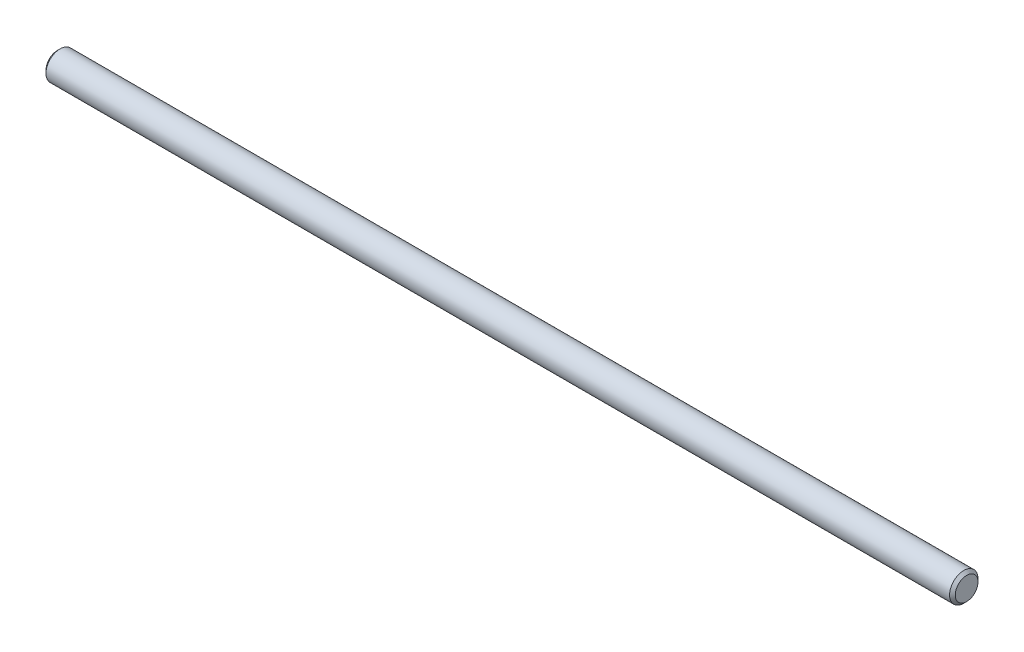
SolidWorks part; units mm, degrees
ref_plane "Front" through (0, 0, 0) normal (0, 0, 1) x (1, 0, 0)
ref_plane "Top" through (0, 0, 0) normal (0, 1, 0) x (1, 0, 0)
ref_plane "Right" through (0, 0, 0) normal (1, 0, 0) x (0, 0, -1)
sketch "Sketch1" plane through (0, 0, 0) normal (0, 0, 1) x (1, 0, 0)
  line L0 (-203.2, 0) -> (203.2, 0) construction
  line L1 (203.2, 6.35) -> (203.2, -6.35) construction
  line L2 (-203.2, 6.35) -> (-203.2, -6.35) construction
  dimension "Length" = 406.4
  dimension "Diameter" = 12.7
sketch "Sketch2" plane through (0, 0, 0) normal (1, 0, 0) x (0, 0, -1)
  circle A0 centre (0, 0) radius 6.35
extrude "Extrude1" add sketch "Sketch2" against normal up to vertex (203.2 mm away) and the other way up to vertex (203.2 mm away) up to point (-203.2, 6.35, 0) other way up to point (203.2, 6.35, 0)
chamfer "Chamfer1" distance 1.27 angle 45 2 edges at (203.2, 0, -6.35) (-203.2, 0, -6.35)
equation "\"D1@Chamfer1\" = \"Diameter@Sketch1\"*.1"
